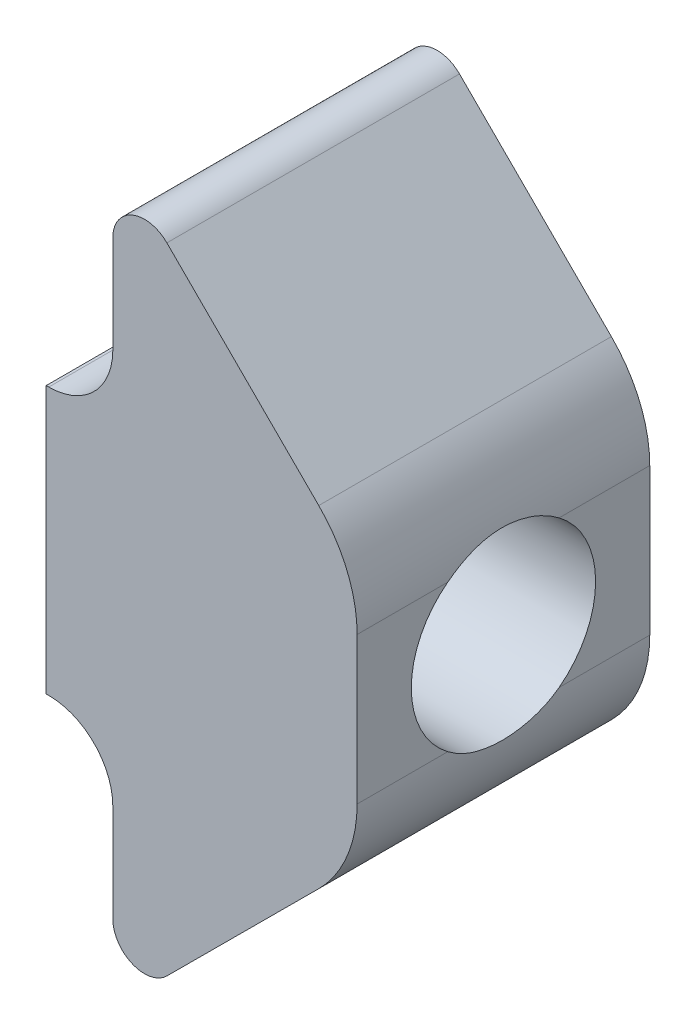
SolidWorks part; units mm, degrees
ref_plane "Front Plane" through (0, 0, 0) normal (0, 0, 1) x (1, 0, 0)
ref_plane "Top Plane" through (0, 0, 0) normal (0, 1, 0) x (1, 0, 0)
ref_plane "Right Plane" through (0, 0, 0) normal (1, 0, 0) x (0, 0, -1)
sketch "Sketch1" plane through (0, 0, 0) normal (0, 0, 1) x (1, 0, 0)
  line L0 (-11.5951, -2.8985) -> (-11.5951, 2.8985)
  line L1 (-11.5951, 2.8985) -> (-11.5392, 2.8985)
  line L2 (-10.1502, 4.2875) -> (-10.1502, 6.4021)
  line L3 (-8.9773, 6.8887) -> (-5.6811, 3.6001)
  line L4 (-4.8485, 1.5932) -> (-4.8485, -1.5932)
  line L5 (-5.6811, -3.6001) -> (-8.9773, -6.8887)
  line L6 (-10.1502, -6.4021) -> (-10.1502, -4.2875)
  line L7 (-11.5392, -2.8985) -> (-11.5951, -2.8985)
  line L8 (-11.651, 2.8985) -> (-11.5392, 2.8985) construction
  line L9 (-11.5392, -2.8985) -> (-11.651, -2.8985) construction
  line L10 (-11.5951, -2.8985) -> (-11.9739, -2.8985)
  line L119 (-11.651, 3.2385) -> (-11.5392, 3.2385) construction
  line L120 (-10.4902, 4.2875) -> (-10.4902, 6.4021) construction
  line L121 (-8.7371, 7.1294) -> (-5.441, 3.8408) construction
  line L122 (-4.5085, 1.5932) -> (-4.5085, -1.5932) construction
  line L123 (-5.441, -3.8408) -> (-8.7371, -7.1294) construction
  line L124 (-10.4902, -6.4021) -> (-10.4902, -4.2875) construction
  line L125 (-11.5392, -3.2385) -> (-11.651, -3.2385) construction
  arc A0 (-11.5392, 2.8985) -> (-10.1502, 4.2875) centre (-11.5392, 4.2875) ccw
  arc A1 (-8.9773, 6.8887) -> (-10.1502, 6.4021) centre (-9.4628, 6.4021) ccw
  arc A2 (-4.8485, 1.5932) -> (-5.6811, 3.6001) centre (-7.6835, 1.5932) ccw
  arc A3 (-5.6811, -3.6001) -> (-4.8485, -1.5932) centre (-7.6835, -1.5932) ccw
  arc A4 (-10.1502, -6.4021) -> (-8.9773, -6.8887) centre (-9.4628, -6.4021) ccw
  arc A5 (-10.1502, -4.2875) -> (-11.5392, -2.8985) centre (-11.5392, -4.2875) ccw
  arc A142 (-11.5392, 3.2385) -> (-10.4902, 4.2875) centre (-11.5392, 4.2875) ccw construction
  arc A143 (-8.7371, 7.1294) -> (-10.4902, 6.4021) centre (-9.4628, 6.4021) ccw construction
  arc A144 (-4.5085, 1.5932) -> (-5.441, 3.8408) centre (-7.6835, 1.5932) ccw construction
  arc A145 (-5.441, -3.8408) -> (-4.5085, -1.5932) centre (-7.6835, -1.5932) ccw construction
  arc A146 (-10.4902, -6.4021) -> (-8.7371, -7.1294) centre (-9.4628, -6.4021) ccw construction
  arc A147 (-10.4902, -4.2875) -> (-11.5392, -3.2385) centre (-11.5392, -4.2875) ccw construction
  dimension "D1" = 0.34
  dimension "D2" = 5.7969
  dimension "D3" = 0.3788
extrude "Boss-Extrude1" add sketch "Sketch1" along normal blind 6.35 contours L0 L1 A0 L2 A1 L3 A2 L4 A3 L5 A4 L6 A5 L7
sketch "Sketch2" plane through (-11.5951, 0, 0) normal (-1, 0, 0) x (0, 0, 1)
  line L0 (3.175, 2.8985) -> (3.175, -2.8985) construction
  line L1 (6.35, 2.8985) -> (0, 2.8985) construction
  line L2 (6.35, -2.8985) -> (0, -2.8985) construction
  line L3 (0, 0) -> (6.35, 0) construction
  line L4 (0, -2.8985) -> (0, 2.8985) construction
  line L5 (6.35, -2.8985) -> (6.35, 2.8985) construction
  circle A0 centre (3.175, 0) radius 2
  dimension "D1" = 4
extrude "Cut-Extrude1" cut sketch "Sketch2" against normal up to next contours A0
fillet "Fillet1" radius 0.4 1 edges at (-11.5951, 0, 5.175) profile chamfer
